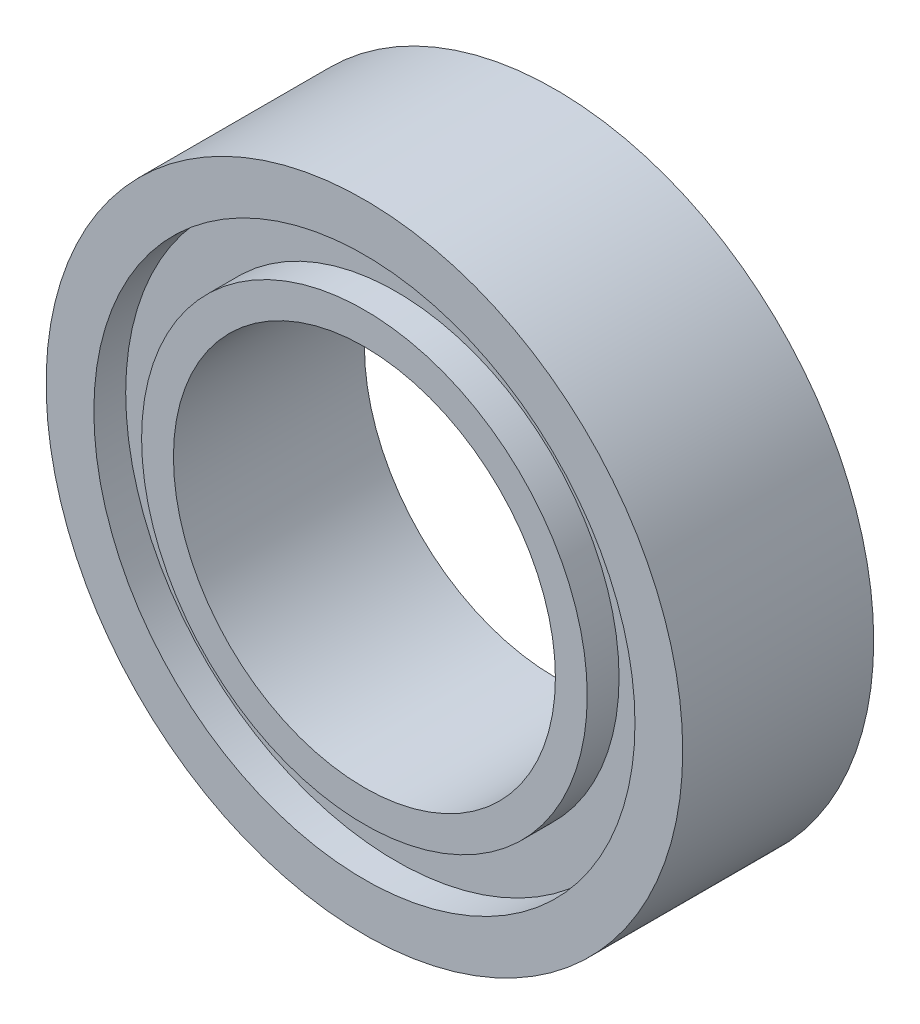
SolidWorks part; units mm, degrees
ref_plane "前视基准面" through (0, 0, 0) normal (0, 0, 1) x (1, 0, 0)
ref_plane "上视基准面" through (0, 0, 0) normal (0, 1, 0) x (1, 0, 0)
ref_plane "右视基准面" through (0, 0, 0) normal (1, 0, 0) x (0, 0, -1)
sketch "草图1" plane through (0, 0, 0) normal (0, 0, 1) x (1, 0, 0)
  circle A0 centre (0, 0) radius 3
  circle A1 centre (0, 0) radius 5
  dimension "D1" = 6
  dimension "D2" = 10
extrude "凸台-拉伸1" add sketch "草图1" along normal blind 3
sketch "草图2" plane through (0, 0, 3) normal (0, 0, 1) x (1, 0, 0)
  circle A0 centre (0, 0) radius 3.5
  circle A1 centre (0, 0) radius 4.25
  dimension "D1" = 7
  dimension "D2" = 8.5
extrude "切除-拉伸1" cut sketch "草图2" against normal blind 0.5
ref_plane "基准面1" through (0, 0, 1.5) normal (0, 0, 1) x (1, 0, 0)
mirror "镜向1" about plane through (0, 0, 1.5) normal (0, 0, 1) of "切除-拉伸1"
